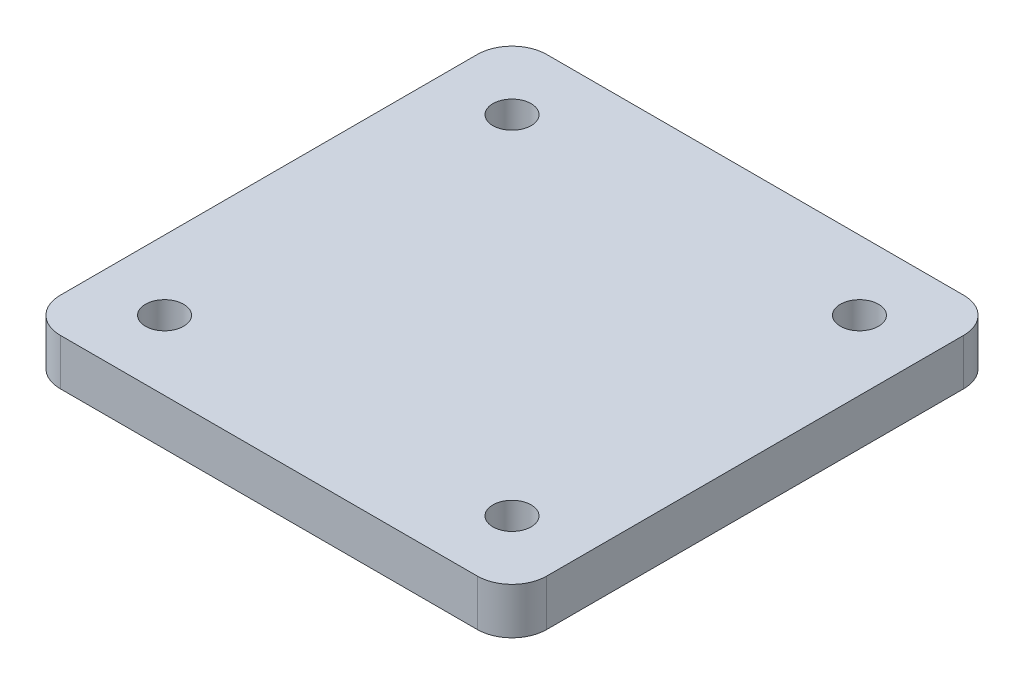
SolidWorks part; units mm, degrees
ref_plane "前视基准面" through (0, 0, 0) normal (0, 0, 1) x (1, 0, 0)
ref_plane "上视基准面" through (0, 0, 0) normal (0, 1, 0) x (1, 0, 0)
ref_plane "右视基准面" through (0, 0, 0) normal (1, 0, 0) x (0, 0, -1)
other "Configuration Table"
sketch "草图1" plane through (0, 0, 0) normal (0, 0, 1) x (1, 0, 0)
  line L0 (0, 0) -> (42, 0)
  line L1 (42, 0) -> (42, 4)
  line L2 (42, 4) -> (0, 4)
  line L3 (0, 4) -> (0, 0)
  dimension "width" = 42
  dimension "height" = 4
extrude "BlockExtrude" add sketch "草图1" along normal blind 42
fillet "Fillet" radius 3 4 edges at (0, 2, 0) (42, 2, 0) (0, 2, 42) (42, 2, 42)
sketch "草图2" plane through (0, 4, 0) normal (0, 1, 0) x (1, 0, 0)
  circle A0 centre (6, -6) radius 1.65
  dimension "diameter" = 3.3
  dimension "x" = 6
  dimension "y" = 6
extrude "Mount_hole" cut sketch "草图2" against normal through all
sketch "草图3" plane through (0, 4, 0) normal (0, 1, 0) x (1, 0, 0)
  circle A0 centre (6, -36) radius 1.65
  dimension "diameter" = 3.3
  dimension "x" = 6
  dimension "y" = 36
extrude "切除-拉伸2" cut sketch "草图3" against normal through all
sketch "草图4" plane through (0, 4, 0) normal (0, 1, 0) x (1, 0, 0)
  circle A0 centre (36, -6) radius 1.65
  dimension "diameter" = 3.3
  dimension "x" = 36
  dimension "y" = 6
extrude "切除-拉伸3" cut sketch "草图4" against normal through all
sketch "草图5" plane through (0, 4, 0) normal (0, 1, 0) x (1, 0, 0)
  circle A0 centre (36, -36) radius 1.65
  dimension "diameter" = 3.3
  dimension "x" = 36
  dimension "y" = 36
extrude "切除-拉伸4" cut sketch "草图5" against normal through all
